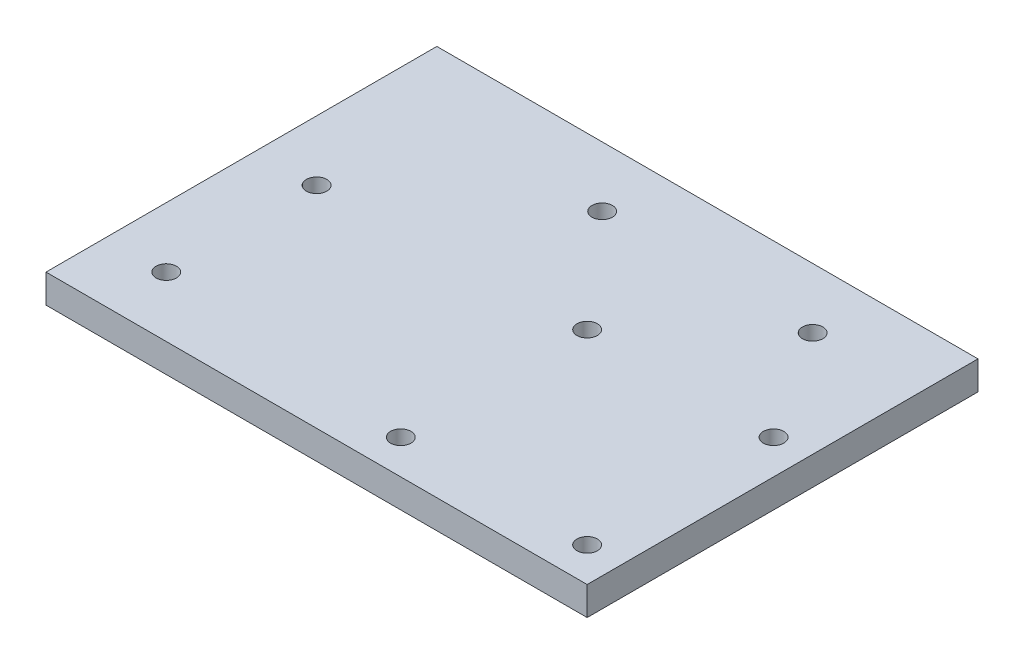
SolidWorks part; units mm, degrees
material "6061 Alloy"
ref_plane "Front Plane" through (0, 0, 0) normal (0, 0, 1) x (1, 0, 0)
ref_plane "Top Plane" through (0, 0, 0) normal (0, 1, 0) x (1, 0, 0)
ref_plane "Right Plane" through (0, 0, 0) normal (1, 0, 0) x (0, 0, -1)
sketch "Sketch1" plane through (0, 0, 0) normal (0, 1, 0) x (1, 0, 0)
  line L1 (0, 0) -> (90, 0)
  line L2 (0, 0) -> (0, 65)
  line L3 (0, 65) -> (90, 65)
  line L4 (90, 0) -> (90, 65)
  dimension "D1" = 90
  dimension "D2" = 65
extrude "Boss-Extrude1" add sketch "Sketch1" along normal blind 4.7625
sketch "Sketch3" plane through (0, 0, 0) normal (0, -1, 0) x (1, 0, 0)
  line L0 (0, -65) -> (0, 0) construction
  line L1 (90, -65) -> (0, -65) construction
  line L2 (10, 0) -> (10, -55) construction
  line L3 (10, -55) -> (90, -55) construction
  line L6 (0, -22.5) -> (10, -22.5) construction
  line L7 (0, 0) -> (90, 0) construction
  line L12 (55, -55) -> (55, -65) construction
  line L13 (90, 0) -> (90, -65) construction
  point P4 (84.291, -36.709)
  point P6 (84.291, -5.709)
  point P12 (53.291, -36.709)
  point P14 (53.291, -5.709)
  point P20 (10, -10)
  point P25 (10, -35)
  point P30 (72.5, -55)
  point P31 (37.5, -55)
  dimension "D1" = 10
  dimension "D2" = 10
  dimension "D3" = 22.5
  dimension "D4" = 10
  dimension "D5" = 35
  dimension "D6" = 17.5
hole_wizard "M3 Clearance Hole1" positions "Sketch4" profile "Sketch5" hole size "M3" standard "ANSI Metric" end condition through all
sketch "Sketch4" plane through (0, 4.7625, 0) normal (0, 1, 0) x (1, 0, 0)
  point P0 (84.291, 5.709)
  point P3 (84.291, 36.709)
  point P6 (53.291, 36.709)
  point P9 (53.291, 5.709)
sketch "Sketch5" plane through (84.291, 4.7625, -5.709) normal (1, 0, 0) x (0, 0, 1)
  line L0 (0, 0) -> (0, 4.7625)
  line L1 (0, 4.7625) -> (1.7, 4.7625)
  line L2 (1.7, 4.7625) -> (1.7, 0)
  line L5 (1.7, 0) -> (0, 0)
  line L11 (0, -6.35) -> (0, 107.95) construction
  dimension "Thru Hole Dia." = 3.4
  dimension "Thru Hole Depth" = 4.7625
hole_wizard "M3 Clearance Hole2" positions "Sketch6" profile "Sketch7" hole size "M3" standard "ANSI Metric" end condition through all
sketch "Sketch6" plane through (0, 0, 0) normal (0, -1, 0) x (-1, 0, 0)
  point P0 (-37.5, 55)
  point P3 (-72.5, 55)
  point P6 (-10, 35)
  point P9 (-10, 10)
sketch "Sketch7" plane through (37.5, 0, -55) normal (1, 0, 0) x (0, 0, -1)
  line L0 (0, 0) -> (0, 4.7625)
  line L1 (0, 4.7625) -> (1.7, 4.7625)
  line L2 (1.7, 4.7625) -> (1.7, 0)
  line L5 (1.7, 0) -> (0, 0)
  line L11 (0, -6.35) -> (0, 107.95) construction
  dimension "Thru Hole Dia." = 3.4
  dimension "Thru Hole Depth" = 4.7625
